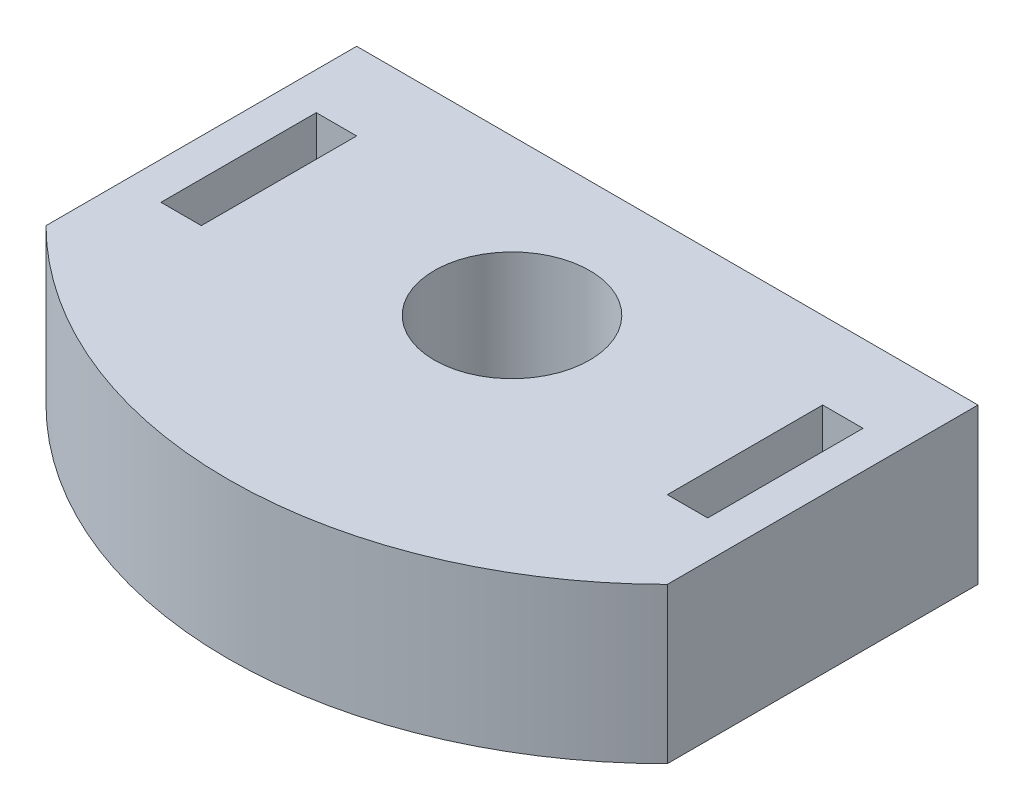
SolidWorks part; units mm, degrees
ref_plane "Front Plane" through (0, 0, 0) normal (0, 0, 1) x (1, 0, 0)
ref_plane "Top Plane" through (0, 0, 0) normal (0, 1, 0) x (1, 0, 0)
ref_plane "Right Plane" through (0, 0, 0) normal (1, 0, 0) x (0, 0, -1)
sketch "Sketch1" plane through (0, 0, 0) normal (0, 1, 0) x (1, 0, 0)
  line L0 (0, -10) -> (0, -15.4389) construction
  line L1 (-20, -10) -> (20, -10)
  line L2 (-20, -10) -> (-20, 10)
  line L3 (-20, 10) -> (20, 10)
  line L4 (20, -10) -> (20, 10)
  line L5 (-20, -10) -> (20, 10) construction
  line L6 (-20, 10) -> (20, -10) construction
  line L8 (-15, 0) -> (0, 0) construction
  line L9 (-17.6, -5) -> (-15, -5)
  line L10 (-17.6, -5) -> (-17.6, 5)
  line L11 (-17.6, 5) -> (-15, 5)
  line L12 (-15, -5) -> (-15, 5)
  line L13 (-17.6, -5) -> (-15, 5) construction
  line L14 (-17.6, 5) -> (-15, -5) construction
  line L15 (15, -5) -> (17.6, -5)
  line L16 (15, -5) -> (15, 5)
  line L17 (15, 5) -> (17.6, 5)
  line L18 (17.6, -5) -> (17.6, 5)
  line L19 (15, -5) -> (17.6, 5) construction
  line L20 (15, 5) -> (17.6, -5) construction
  line L21 (0, 0) -> (15, 0) construction
  circle A0 centre (0, 0) radius 5
  arc A1 (-20, -10) -> (20, -10) centre (0, 10) ccw
  point P0 (0, 0)
  point P13 (-16.3, 0)
  point P18 (16.3, 0)
  dimension "D3" = 10
  dimension "D4" = 20
  dimension "D1" = 40
  dimension "D2" = 20
  dimension "D5" = 15
  dimension "D6" = 2.6
  dimension "D7" = 10
extrude "Boss-Extrude1" add sketch "Sketch1" along normal blind 10 contours L1 L4 L3 L2 A0 L18 L15 L16 L17 L12 L9 L10 L11 | L1 A1
